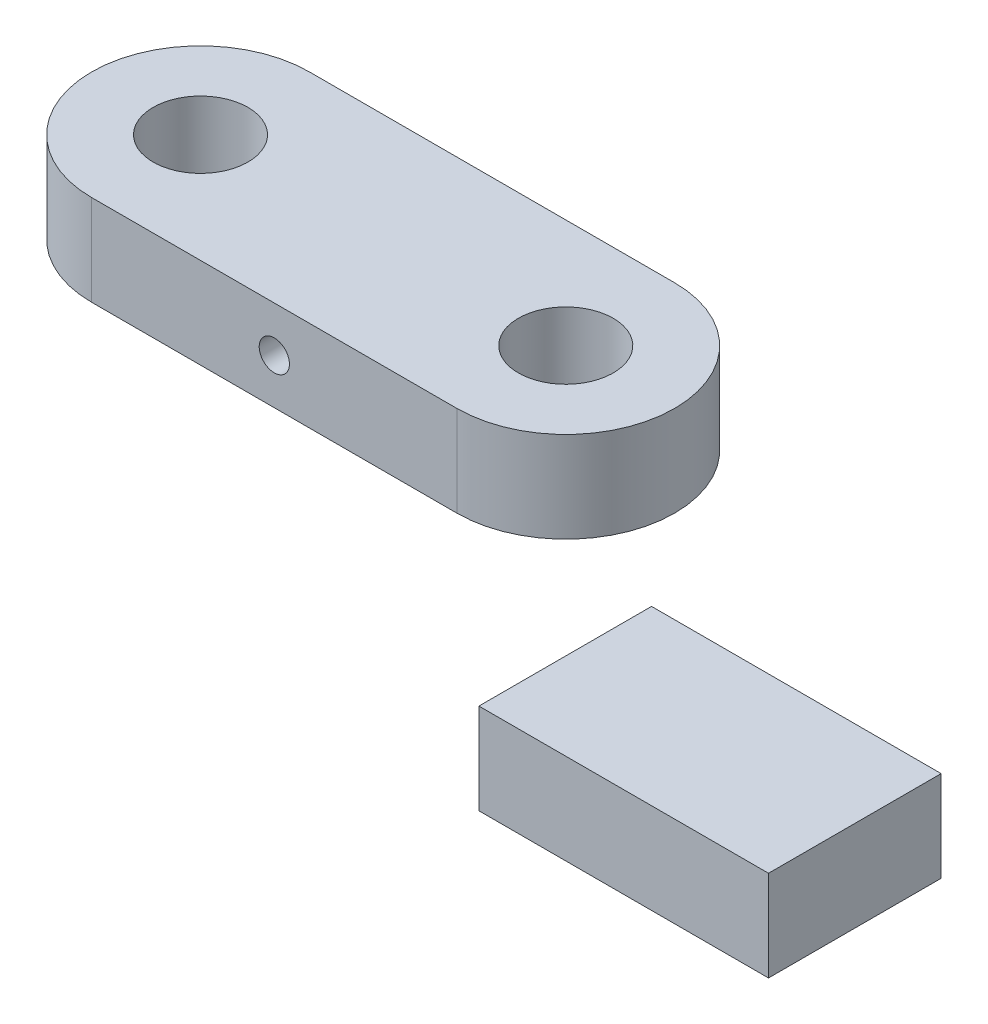
SolidWorks part; units mm, degrees
material "6061-T6 (SS)"
ref_plane "Front Plane" through (0, 0, 0) normal (0, 0, 1) x (1, 0, 0)
ref_plane "Top Plane" through (0, 0, 0) normal (0, 1, 0) x (1, 0, 0)
ref_plane "Right Plane" through (0, 0, 0) normal (1, 0, 0) x (0, 0, -1)
sketch "Sketch4" plane through (0, 0, 0) normal (0, 1, 0) x (1, 0, 0)
  line L0 (0, 0) -> (19.177, 0) construction
  line L1 (0, 5.715) -> (19.177, 5.715)
  line L2 (0, -5.715) -> (19.177, -5.715)
  arc A0 (0, 5.715) -> (0, -5.715) centre (0, 0) ccw
  arc A1 (19.177, -5.715) -> (19.177, 5.715) centre (19.177, 0) ccw
  circle A2 centre (0, 0) radius 2.4892
  circle A3 centre (19.177, 0) radius 2.4892
  point P3 (9.5885, 0)
  dimension "D1" = 4.9784
  dimension "D2" = 5.715
  dimension "D3" = 19.177
extrude "Boss-Extrude1" add sketch "Sketch4" along normal blind 4.7625
sketch "Sketch5" plane through (0, 0, 5.715) normal (0, 0, 1) x (1, 0, 0)
  line L0 (9.5885, 0) -> (9.5885, 4.7625) construction
  line L1 (0, 0) -> (19.177, 0) construction
  line L2 (0, 4.7625) -> (19.177, 4.7625) construction
  circle A0 centre (9.5885, 2.3812) radius 0.7937
  dimension "D1" = 1.5875
extrude "Cut-Extrude4" cut sketch "Sketch5" against normal through all both and the other way through all
sketch "Sketch6" plane through (0, 0, 0) normal (0, -1, 0) x (1, 0, 0)
  line L1 (33.2853, 18.6695) -> (48.4896, 18.6695)
  line L2 (33.2853, 18.6695) -> (33.2853, 9.6061)
  line L3 (33.2853, 9.6061) -> (48.4896, 9.6061)
  line L4 (48.4896, 18.6695) -> (48.4896, 9.6061)
  line L5 (33.2853, 18.6695) -> (48.4896, 9.6061) construction
  line L6 (33.2853, 9.6061) -> (48.4896, 18.6695) construction
  point P4 (40.8875, 14.1378)
extrude "Boss-Extrude2" add sketch "Sketch6" against normal up to surface (4.7625 mm away) separate body up to face at (0, 4.7625, 2.4892)
